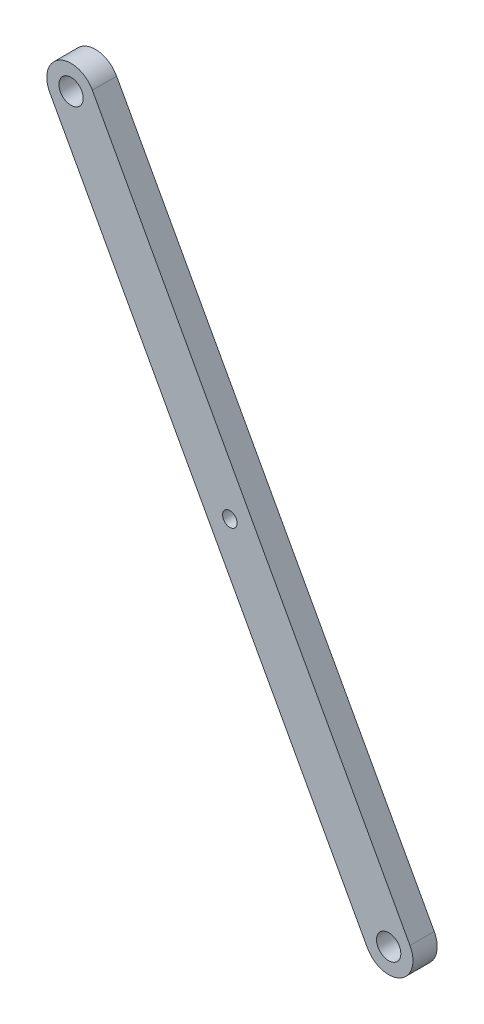
SolidWorks part; units mm, degrees
ref_plane "Plan de face" through (0, 0, 0) normal (0, 0, 1) x (1, 0, 0)
ref_plane "Plan de dessus" through (0, 0, 0) normal (0, 1, 0) x (1, 0, 0)
ref_plane "Plan de droite" through (0, 0, 0) normal (1, 0, 0) x (0, 0, -1)
sketch "Esquisse1" plane through (0, 0, 0) normal (0, 0, 1) x (1, 0, 0)
  line L0 (97.5204, -9.6831) -> (162.9429, -129.5459) construction
  line L1 (101.9093, -7.2876) -> (167.3317, -127.1504)
  line L2 (93.1316, -12.0785) -> (158.5541, -131.9413)
  arc A0 (101.9093, -7.2876) -> (93.1316, -12.0785) centre (97.5204, -9.6831) ccw
  arc A1 (158.5541, -131.9413) -> (167.3317, -127.1504) centre (162.9429, -129.5459) ccw
  circle A2 centre (97.5204, -9.6831) radius 2.5
  circle A3 centre (162.9429, -129.5459) radius 2.5
  point P4 (130.2317, -69.6145)
  dimension "D1" = 5
extrude "Boss.-Extru.1" add sketch "Esquisse1" along normal blind 5
sketch "Esquisse2" plane through (0, 0, 5) normal (0, 0, 1) x (1, 0, 0)
  line L0 (97.5204, -9.6831) -> (162.9429, -129.5459) construction
  circle A0 centre (130.2317, -69.6145) radius 1.5
  dimension "D1" = 3
extrude "Enlèv. mat.-Extru.1" cut sketch "Esquisse2" against normal through all
